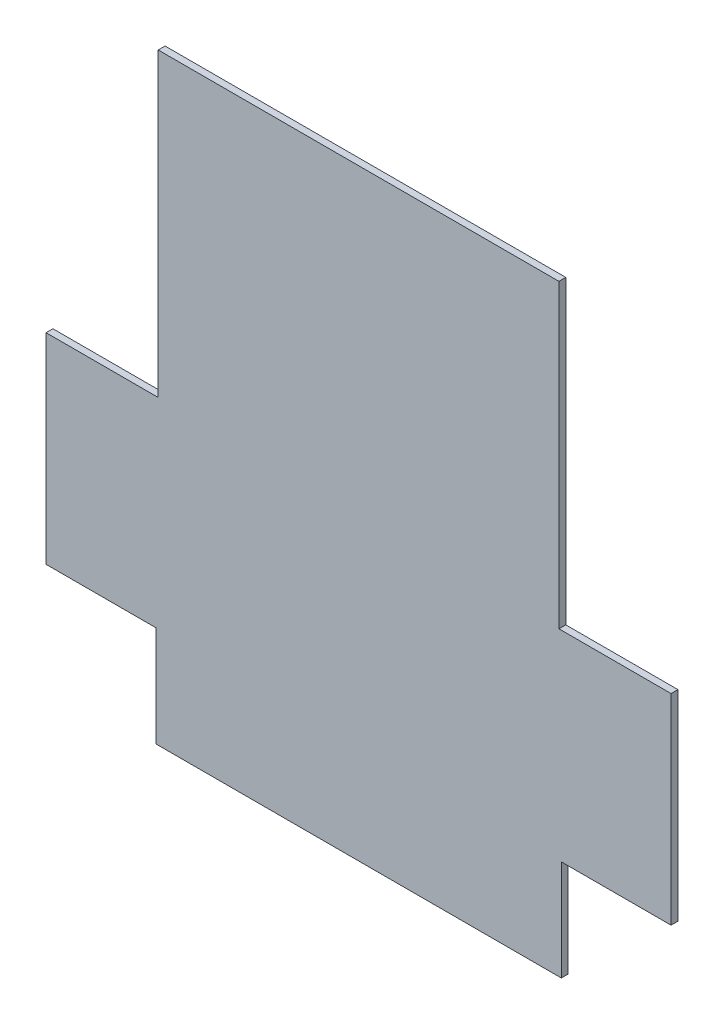
SolidWorks part; units mm, degrees
material "Oak"
ref_plane "Front Plane" through (0, 0, 0) normal (0, 0, 1) x (1, 0, 0)
ref_plane "Top Plane" through (0, 0, 0) normal (0, 1, 0) x (1, 0, 0)
ref_plane "Right Plane" through (0, 0, 0) normal (1, 0, 0) x (0, 0, -1)
sketch "Sketch1" plane through (0, 0, 0) normal (0, 0, 1) x (1, 0, 0)
  line L1 (0, 0) -> (273.4, 0)
  line L2 (0, 0) -> (0, -263.4)
  line L3 (0, -263.4) -> (273.4, -263.4)
  line L4 (273.4, 0) -> (273.4, -263.4)
  dimension "D1" = 273.4
  dimension "D2" = 263.4
extrude "Boss-Extrude1" add sketch "Sketch1" along normal blind 3
sketch "Sketch2" plane through (0, 0, 3) normal (0, 0, 1) x (1, 0, 0)
  line L1 (0, 0) -> (49.05, 0)
  line L2 (0, 0) -> (0, -131.64)
  line L3 (0, -131.64) -> (49.05, -131.64)
  line L4 (49.05, 0) -> (49.05, -131.64)
  line L5 (0, -263.4) -> (48, -263.4)
  line L6 (0, -263.4) -> (0, -219.4)
  line L7 (0, -219.4) -> (48, -219.4)
  line L8 (48, -263.4) -> (48, -219.4)
  line L9 (273.4, 0) -> (224.35, 0)
  line L10 (273.4, 0) -> (273.4, -131.64)
  line L11 (273.4, -131.64) -> (224.35, -131.64)
  line L12 (224.35, 0) -> (224.35, -131.64)
  line L13 (273.4, -263.4) -> (225.4, -263.4)
  line L14 (273.4, -263.4) -> (273.4, -219.4)
  line L15 (273.4, -219.4) -> (225.4, -219.4)
  line L16 (225.4, -263.4) -> (225.4, -219.4)
  dimension "D1" = 49.05
  dimension "D2" = 131.64
  dimension "D3" = 48
  dimension "D4" = 44
  dimension "D5" = 49.05
  dimension "D6" = 131.64
  dimension "D7" = 48
  dimension "D8" = 44
extrude "Cut-Extrude1" cut sketch "Sketch2" against normal through all
